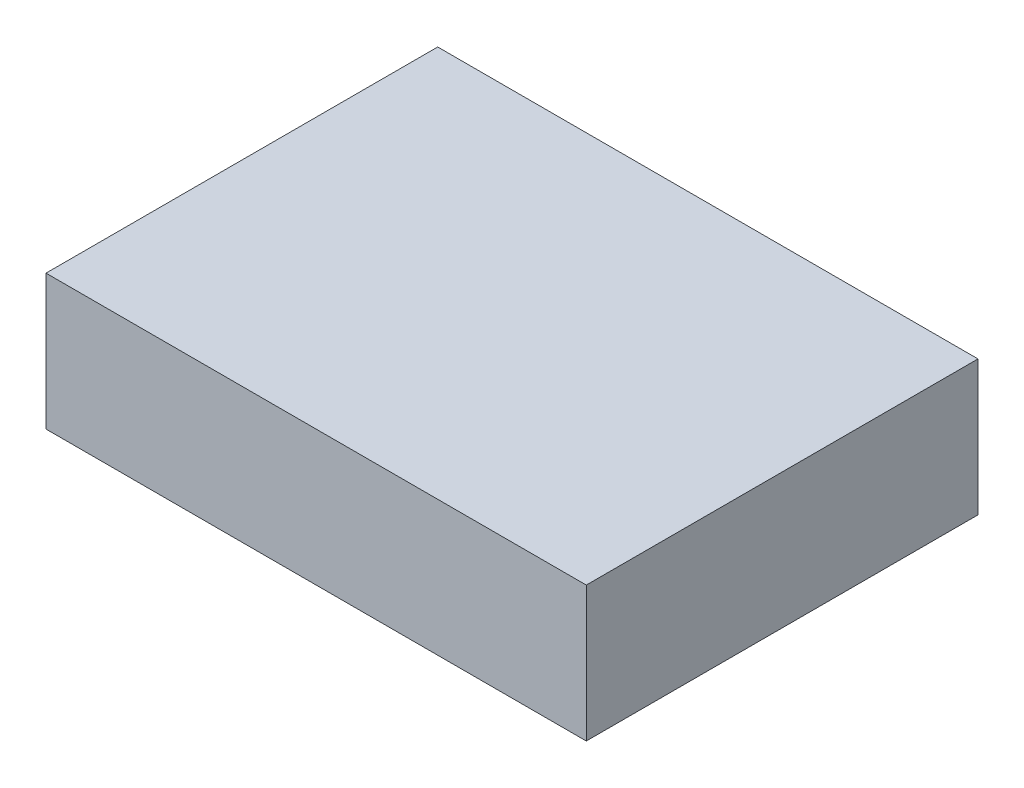
SolidWorks part; units mm, degrees
ref_plane "Front Plane" through (0, 0, 0) normal (0, 0, 1) x (1, 0, 0)
ref_plane "Top Plane" through (0, 0, 0) normal (0, 1, 0) x (1, 0, 0)
ref_plane "Right Plane" through (0, 0, 0) normal (1, 0, 0) x (0, 0, -1)
sketch "Sketch1" plane through (0, 0, 0) normal (0, 1, 0) x (1, 0, 0)
  line L1 (0, 0) -> (40, 0)
  line L2 (0, 0) -> (0, 29)
  line L3 (0, 29) -> (40, 29)
  line L4 (40, 0) -> (40, 29)
extrude "Boss-Extrude1" add sketch "Sketch1" against normal blind 10
